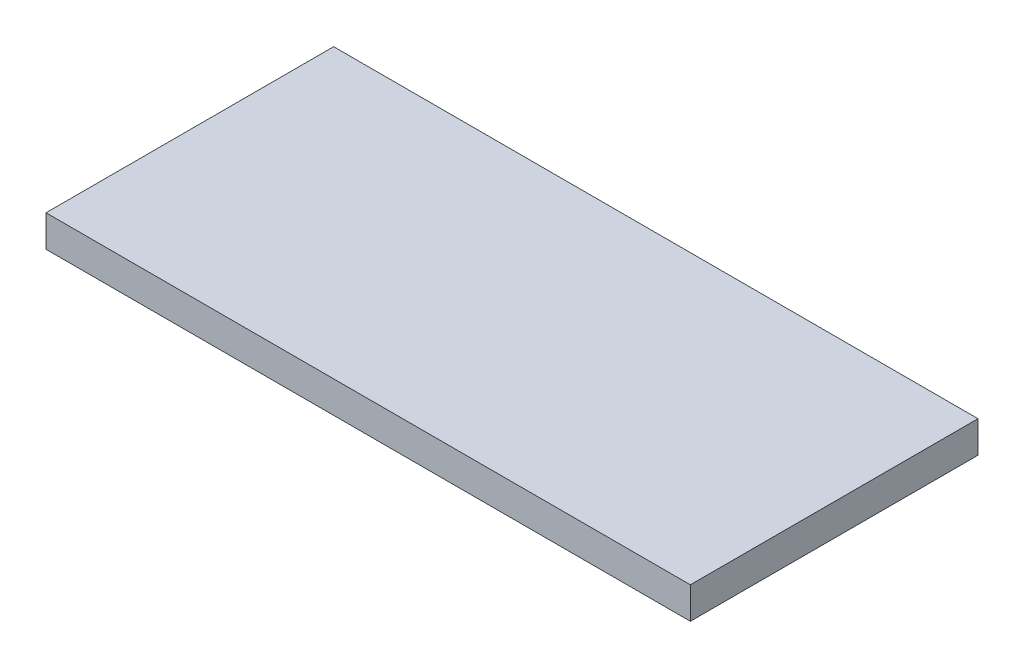
SolidWorks part; units mm, degrees
ref_plane "Front Plane" through (0, 0, 0) normal (0, 0, 1) x (1, 0, 0)
ref_plane "Top Plane" through (0, 0, 0) normal (0, 1, 0) x (1, 0, 0)
ref_plane "Right Plane" through (0, 0, 0) normal (1, 0, 0) x (0, 0, -1)
sketch "Sketch1" plane through (0, 0, 0) normal (0, 1, 0) x (1, 0, 0)
  line L1 (-142.24, -63.5) -> (142.24, -63.5)
  line L2 (-142.24, -63.5) -> (-142.24, 63.5)
  line L3 (-142.24, 63.5) -> (142.24, 63.5)
  line L4 (142.24, -63.5) -> (142.24, 63.5)
  line L5 (-142.24, -63.5) -> (142.24, 63.5) construction
  line L6 (-142.24, 63.5) -> (142.24, -63.5) construction
  point P0 (0, 0)
  dimension "D1" = 284.48
  dimension "D2" = 127
extrude "Boss-Extrude1" add sketch "Sketch1" along normal blind 13.97
